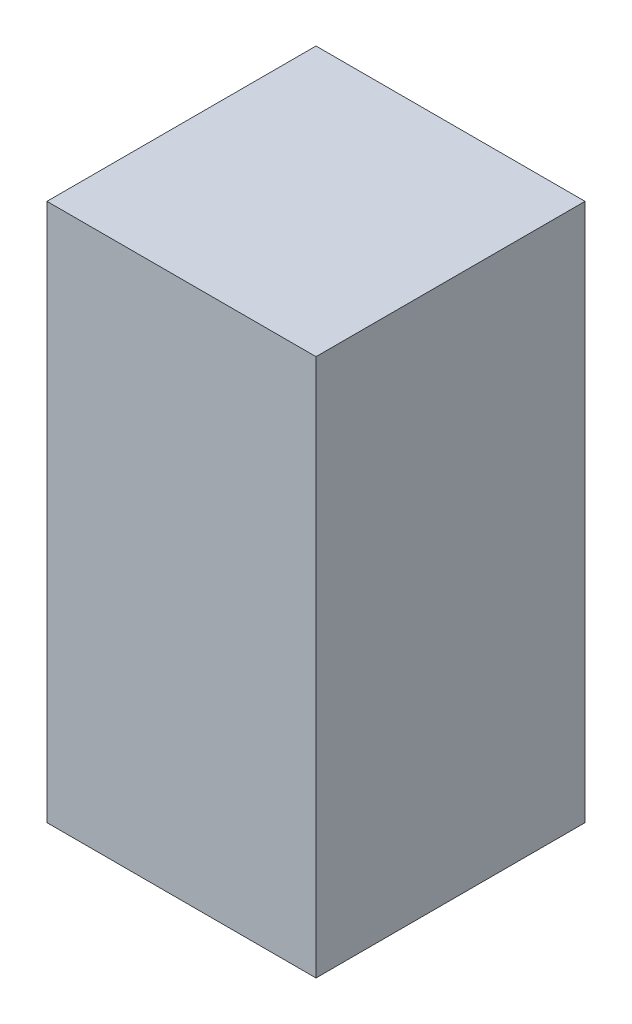
SolidWorks part; units mm, degrees
material "Pine"
ref_plane "Front Plane" through (0, 0, 0) normal (0, 0, 1) x (1, 0, 0)
ref_plane "Top Plane" through (0, 0, 0) normal (0, 1, 0) x (1, 0, 0)
ref_plane "Right Plane" through (0, 0, 0) normal (1, 0, 0) x (0, 0, -1)
sketch "Sketch1" plane through (0, 0, 0) normal (0, 1, 0) x (1, 0, 0)
  line L1 (0, 0) -> (10, 0)
  line L2 (0, 0) -> (0, 10)
  line L3 (0, 10) -> (10, 10)
  line L4 (10, 0) -> (10, 10)
  dimension "D1" = 10
  dimension "D2" = 10
extrude "Boss-Extrude1" add sketch "Sketch1" along normal blind 20
equation "\"BoardThickness\"=20"
equation "\"D1@Boss-Extrude1\"=\"BoardThickness\""
